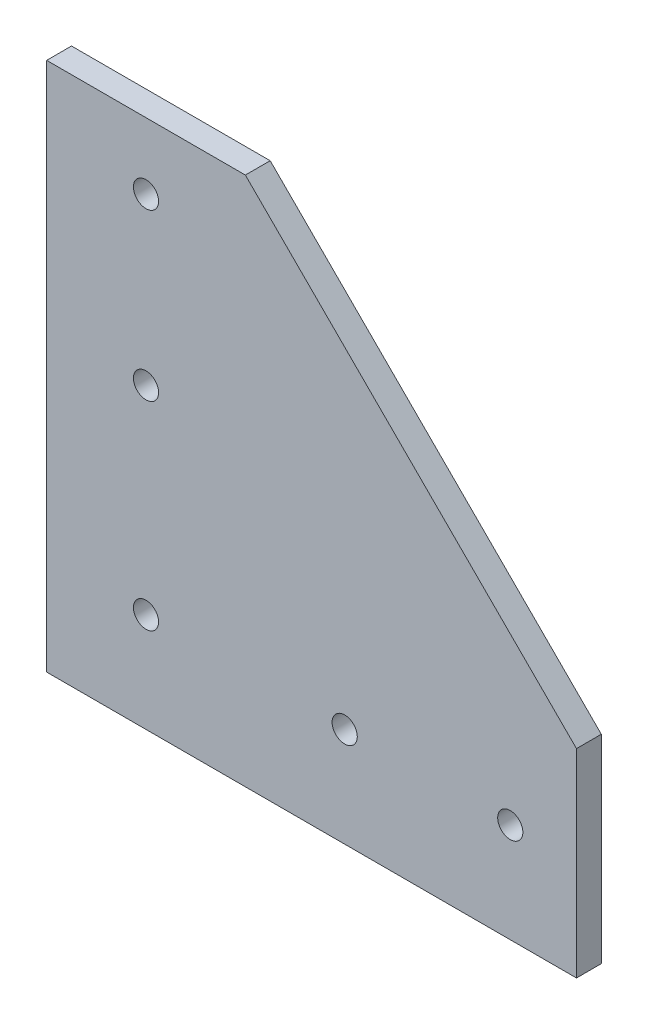
SolidWorks part; units mm, degrees
ref_plane "Front Plane" through (0, 0, 0) normal (0, 0, 1) x (1, 0, 0)
ref_plane "Top Plane" through (0, 0, 0) normal (0, 1, 0) x (1, 0, 0)
ref_plane "Right Plane" through (0, 0, 0) normal (1, 0, 0) x (0, 0, -1)
sketch "Sketch1" plane through (0, 0, 0) normal (0, 0, 1) x (1, 0, 0)
  line L0 (38.1, 101.6) -> (101.6, 38.1)
  line L1 (0, 0) -> (101.6, 0)
  line L2 (0, 0) -> (0, 101.6)
  line L3 (0, 101.6) -> (101.6, 101.6)
  line L4 (101.6, 0) -> (101.6, 101.6)
  circle A0 centre (19.05, 19.05) radius 2.413
  circle A1 centre (19.05, 57.15) radius 2.413
  circle A2 centre (19.05, 88.9) radius 2.413
  circle A3 centre (88.9, 19.05) radius 2.413
  circle A4 centre (57.15, 19.05) radius 2.413
  dimension "D6" = 4.826
  dimension "D12" = 4.826
  dimension "D13" = 4.826
  dimension "D14" = 4.826
  dimension "D15" = 4.826
  dimension "D1" = 101.6
  dimension "D2" = 101.6
  dimension "D3" = 38.1
  dimension "D4" = 38.1
  dimension "D5" = 12.7
  dimension "D7" = 19.05
  dimension "D8" = 38.1
  dimension "D9" = 19.05
  dimension "D10" = 19.05
  dimension "D11" = 19.05
  dimension "D16" = 12.7
  dimension "D17" = 31.75
  dimension "D18" = 19.05
  dimension "D19" = 19.05
extrude "Boss-Extrude1" add sketch "Sketch1" along normal blind 4.7625 contours L1 L4 L0 L3 L2 A4 A3 A2 A1 A0
